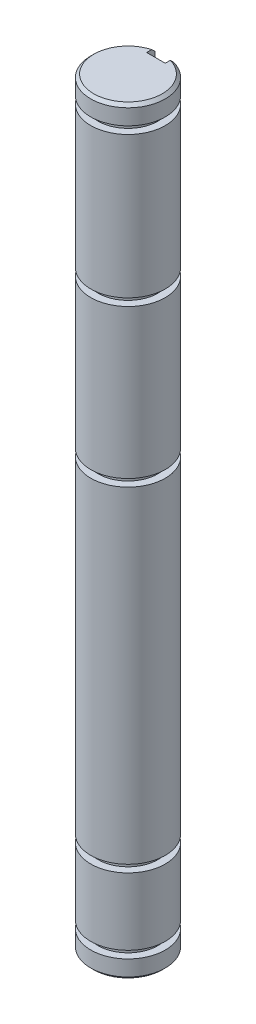
SolidWorks part; units mm, degrees
ref_plane "Front" through (0, 0, 0) normal (0, 0, 1) x (1, 0, 0)
ref_plane "Top" through (0, 0, 0) normal (0, 1, 0) x (1, 0, 0)
ref_plane "Right" through (0, 0, 0) normal (1, 0, 0) x (0, 0, -1)
sketch "Sketch1" plane through (0, 0, 0) normal (0, 0, 1) x (1, 0, 0)
  line L0 (6.35, 64.1668) -> (5.842, 64.6748)
  line L1 (5.842, -64.6748) -> (0, -64.6748)
  line L2 (6.35, -64.1668) -> (6.35, -61.4997)
  line L3 (5.842, 64.6748) -> (0, 64.6748)
  line L4 (0, -64.6748) -> (0, 64.6748)
  line L5 (6.35, -64.1668) -> (5.842, -64.6748)
  line L6 (6.35, 61.4998) -> (6.35, 64.1668)
  line L7 (6.35, 61.4998) -> (5.08, 61.4998)
  line L8 (6.35, -60.2297) -> (6.35, -48.7997)
  line L9 (6.35, 60.2298) -> (5.08, 60.2298)
  line L10 (5.08, 61.4998) -> (5.08, 60.2298)
  line L11 (6.35, -61.4997) -> (5.08, -61.4997)
  line L12 (6.35, 36.0998) -> (6.35, 60.2298)
  line L13 (6.35, -60.2297) -> (5.08, -60.2297)
  line L14 (5.08, -61.4997) -> (5.08, -60.2297)
  line L15 (6.35, 36.0998) -> (5.08, 36.0998)
  line L16 (6.35, 9.4298) -> (6.35, 34.8298)
  line L17 (6.35, 34.8298) -> (5.08, 34.8298)
  line L18 (5.08, 36.0998) -> (5.08, 34.8298)
  line L19 (6.35, 9.4298) -> (5.08, 9.4298)
  line L20 (6.35, -47.5297) -> (6.35, 8.1598)
  line L21 (6.35, 8.1598) -> (5.08, 8.1598)
  line L22 (5.08, 9.4298) -> (5.08, 8.1598)
  line L23 (6.35, -47.5297) -> (5.08, -47.5297)
  line L25 (6.35, -48.7997) -> (5.08, -48.7997)
  line L26 (5.08, -47.5297) -> (5.08, -48.7997)
  point P0 (6.35, -64.6748)
  point P2 (6.35, 64.6748)
  point P4 (0, 0)
  dimension "D2" = 6.35
  dimension "D5" = 0.508
  dimension "D6" = 0.508
  dimension "D3" = 3.175
  dimension "D4" = 1.27
  dimension "D7" = 1.27
  dimension "D8" = 3.175
  dimension "D9" = 25.4
  dimension "D10" = 25.4
  dimension "D11" = 82.3595
  dimension "D12" = 12.7
revolve "Revolve1" add sketch "Sketch1" angle 360 about L4
sketch "Sketch2" plane through (0, 64.6748, 0) normal (0, 1, 0) x (1, 0, 0)
  line L1 (-1.5875, 6.35) -> (1.5875, 6.35)
  line L2 (-1.5875, 6.35) -> (-1.5875, 4.7625)
  line L3 (-1.5875, 4.7625) -> (1.5875, 4.7625)
  line L4 (1.5875, 6.35) -> (1.5875, 4.7625)
  circle A0 centre (0, 0) radius 6.35 construction
  point P4 (0, 4.7625)
  dimension "D1" = 4.7625
  dimension "D2" = 3.175
extrude "Cut-Extrude1" cut sketch "Sketch2" against normal through all
